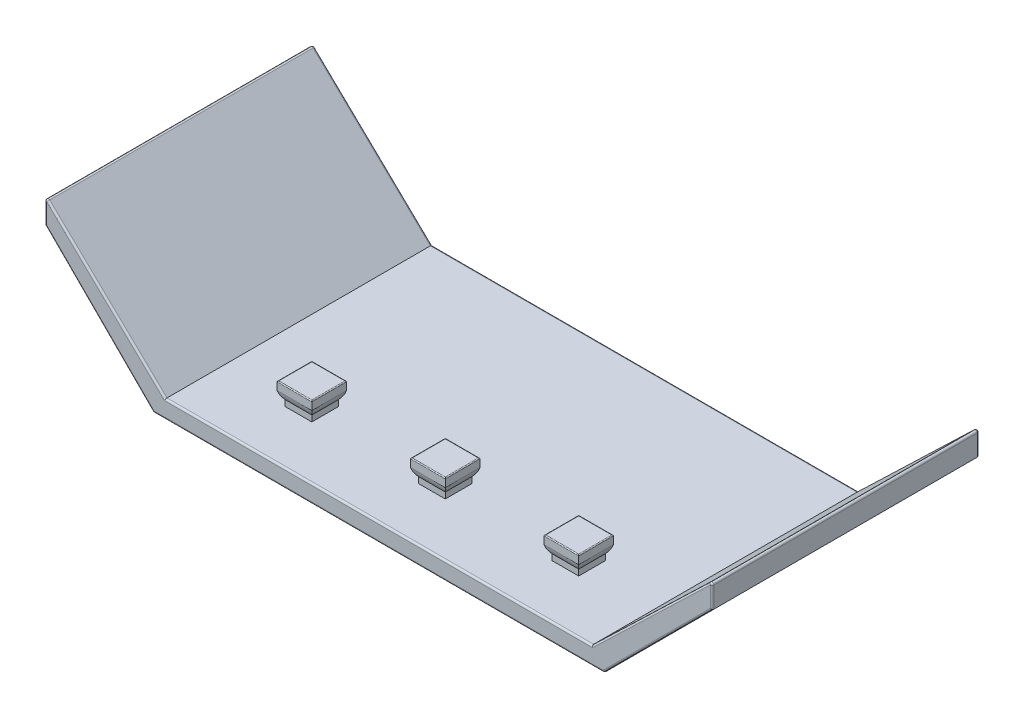
SolidWorks part; units mm, degrees
ref_plane "前视基准面" through (0, 0, 0) normal (0, 0, 1) x (1, 0, 0)
ref_plane "上视基准面" through (0, 0, 0) normal (0, 1, 0) x (1, 0, 0)
ref_plane "右视基准面" through (0, 0, 0) normal (1, 0, 0) x (0, 0, -1)
sketch "草图1" plane through (0, 0, 0) normal (0, 0, 1) x (1, 0, 0)
  line L1 (-25.3284, 0) -> (25.3284, 0)
  line L2 (-23.98, 2) -> (23.98, 2)
  line L3 (37.5, 15) -> (37.5, 12.1716)
  line L4 (0, -4.5046) -> (0, 18.3706) construction
  line L5 (-37.5, 15) -> (-23.98, 2)
  line L6 (-37.5, 12.1716) -> (-25.3284, 0)
  line L7 (-37.5, 15) -> (-37.5, 12.1716)
  line L8 (37.5, 12.1716) -> (25.3284, 0)
  line L9 (37.5, 15) -> (23.98, 2)
  point P11 (0, 0)
  point P12 (0, 15)
  point P14 (0, 2)
extrude "凸台-拉伸1" add sketch "草图1" against normal blind 30
sketch "草图2" plane through (0, 2, 0) normal (0, 1, 0) x (1, 0, 0)
  line L1 (-1.5, 9) -> (1.5, 9)
  line L2 (-1.5, 9) -> (-1.5, 6)
  line L3 (-1.5, 6) -> (1.5, 6)
  line L4 (1.5, 9) -> (1.5, 6)
extrude "凸台-拉伸2" add sketch "草图2" along normal blind 1
sketch "草图3" plane through (0, 0, -6) normal (0, 0, 1) x (1, 0, 0)
  line L1 (-1.95, 4.5) -> (1.95, 4.5)
  line L2 (-1.95, 4.5) -> (-1.95, 3.5556)
  line L3 (-1.5, 3) -> (-1.5, 2) construction
  line L4 (1.95, 4.5) -> (1.95, 3.5556)
  line L5 (-1.5, 2.6771) -> (1.5, 2.6771)
  arc A0 (-1.95, 3.5556) -> (-1.5, 2.6771) centre (0, 4) ccw
  arc A1 (1.5, 2.6771) -> (1.95, 3.5556) centre (0, 4) ccw
extrude "凸台-拉伸3" add sketch "草图3" along normal blind 1 and the other way blind 4
sketch "草图4" plane through (0, 0, 0) normal (1, 0, 0) x (0, 0, -1)
  line L0 (10, 4.5) -> (5, 4.5) construction
  line L1 (10, 4.5) -> (9.45, 4.5)
  line L2 (10, 4.5) -> (10, 2.6771)
  line L3 (10, 2.6771) -> (9, 2.6771)
  line L4 (5, 4.5) -> (5, 2.6771)
  line L5 (10, 3.5556) -> (10, 4.5) construction
  line L6 (6, 2.6771) -> (5, 2.6771) construction
  line L7 (9.45, 4.5) -> (9.45, 3.5556)
  line L8 (5.55, 4.5) -> (5.55, 3.5556)
  line L9 (6, 2.6771) -> (5, 2.6771)
  line L10 (5.55, 4.5) -> (5, 4.5)
  arc A1 (5.55, 3.5556) -> (6, 2.6771) centre (7.5, 4) ccw
  arc A3 (9, 2.6771) -> (9.45, 3.5556) centre (7.5, 4) ccw
extrude "切除-拉伸1" cut sketch "草图4" against normal up to next and the other way up to next
fillet "圆角1" radius 0.1 4 edges at (0, 4.5, -9.45) (1.95, 4.5, -7.5) (0, 4.5, -5.55) (-1.95, 4.5, -7.5)
pattern_linear "阵列(线性)1" count 2 spacing 15 along (1, 0, 0) count 2 spacing 15 along (-1, 0, 0) of "凸台-拉伸2", "凸台-拉伸3", "切除-拉伸1", "圆角1"
fillet "圆角2" radius 0.2 20 edges at (-37.5, 15, -15) (37.5, 15, -15) (-31.4142, 6.0858, -30) (0, 0, -30) (31.4142, 6.0858, -30) (37.5, 13.5858, -30) (30.74, 8.5, -30) (0, 2, -30) (-30.74, 8.5, -30) (-37.5, 13.5858, -30) (-30.74, 8.5, 0) (0, 2, 0) (30.74, 8.5, 0) (37.5, 13.5858, 0) (31.4142, 6.0858, 0) (0, 0, 0) (-31.4142, 6.0858, 0) (-37.5, 13.5858, 0) (25.3284, 0, -15) (-25.3284, 0, -15)
